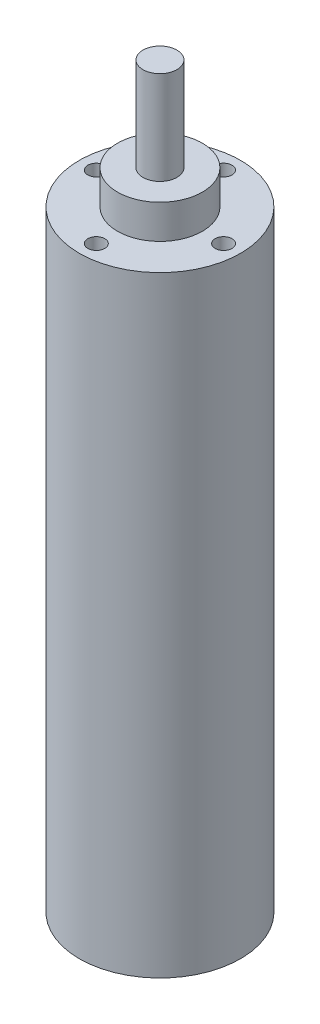
SolidWorks part; units mm, degrees
ref_plane "前视基准面" through (0, 0, 0) normal (0, 0, 1) x (1, 0, 0)
ref_plane "上视基准面" through (0, 0, 0) normal (0, 1, 0) x (1, 0, 0)
ref_plane "右视基准面" through (0, 0, 0) normal (1, 0, 0) x (0, 0, -1)
sketch "草图1" plane through (0, 0, 0) normal (0, 1, 0) x (1, 0, 0)
  circle A0 centre (0, 0) radius 9.5
  dimension "D1" = 19
extrude "凸台-拉伸1" add sketch "草图1" along normal blind 72
sketch "草图2" plane through (0, 72, 0) normal (0, 1, 0) x (1, 0, 0)
  circle A0 centre (0, 0) radius 5
  dimension "D1" = 10
extrude "凸台-拉伸2" add sketch "草图2" along normal blind 4
sketch "草图3" plane through (0, 76, 0) normal (0, 1, 0) x (1, 0, 0)
  circle A0 centre (0, 0) radius 2
  dimension "D1" = 4
extrude "凸台-拉伸3" add sketch "草图3" along normal blind 11
sketch "草图4" plane through (0, 72, 0) normal (0, 1, 0) x (1, 0, 0)
  circle A0 centre (0, 0) radius 9.5 construction
  circle A1 centre (0, 0) radius 9.5
  circle A2 centre (0, 0) radius 7.5 construction
  circle A3 centre (0, -7.5) radius 1
  circle A4 centre (-7.5, 0) radius 1
  circle A5 centre (0, 7.5) radius 1
  circle A6 centre (7.5, 0) radius 1
  point P15 (0, 0)
  dimension "D1" = 2
  dimension "D2" = 2
  dimension "D3" = 4
extrude "切除-拉伸1" cut sketch "草图4" against normal blind 3 contours A6 | A5 | A3 | A4
